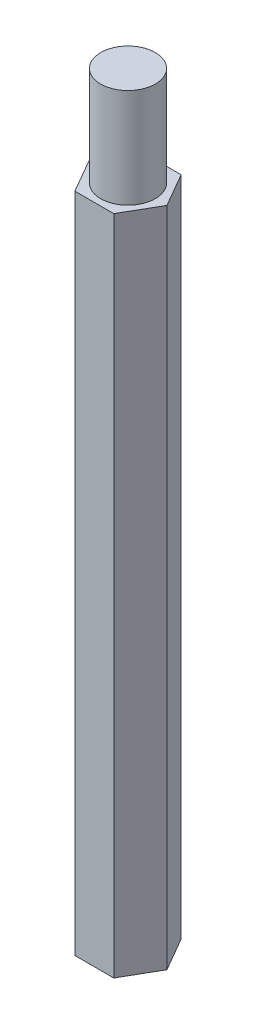
SolidWorks part; units mm, degrees
ref_plane "前视基准面" through (0, 0, 0) normal (0, 0, 1) x (1, 0, 0)
ref_plane "上视基准面" through (0, 0, 0) normal (0, 1, 0) x (1, 0, 0)
ref_plane "右视基准面" through (0, 0, 0) normal (1, 0, 0) x (0, 0, -1)
sketch "草图1" plane through (0, 0, 0) normal (0, 1, 0) x (1, 0, 0)
  line L1 (1.175, 2.0352) -> (-1.175, 2.0352)
  line L2 (-1.175, 2.0352) -> (-2.35, 0)
  line L3 (-2.35, 0) -> (-1.175, -2.0352)
  line L4 (-1.175, -2.0352) -> (1.175, -2.0352)
  line L5 (1.175, -2.0352) -> (2.35, 0)
  line L6 (2.35, 0) -> (1.175, 2.0352)
  circle A0 centre (0, 0) radius 2.0352 construction
  point P1 (1.2133, -2.0126)
  dimension "D1" = 4.7
extrude "凸台-拉伸1" add sketch "草图1" along normal blind 40 contours L1 L2 L3 L4 L5 L6
sketch "草图2" plane through (0, 40, 0) normal (0, 1, 0) x (1, 0, 0)
  circle A0 centre (0, 0) radius 1.65
  dimension "D1" = 3.3
extrude "凸台-拉伸2" add sketch "草图2" along normal blind 6
sketch "草图3" plane through (0, 0, 0) normal (0, -1, 0) x (1, 0, 0)
  circle A0 centre (0, 0) radius 1.65
  dimension "D1" = 3.3
extrude "切除-拉伸1" cut sketch "草图3" against normal blind 6 contours A0
